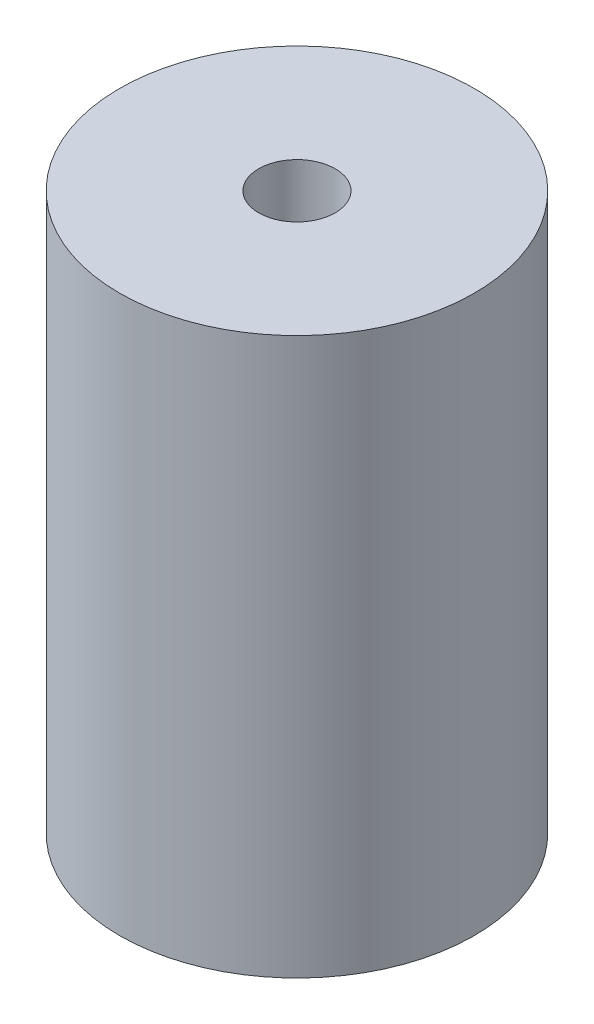
SolidWorks part; units mm, degrees
material "RNX-ELF"
ref_plane "Front Plane" through (0, 0, 0) normal (0, 0, 1) x (1, 0, 0)
ref_plane "Top Plane" through (0, 0, 0) normal (0, 1, 0) x (1, 0, 0)
ref_plane "Right Plane" through (0, 0, 0) normal (1, 0, 0) x (0, 0, -1)
sketch "Sketch1" plane through (0, 0, 0) normal (0, 1, 0) x (1, 0, 0)
  circle A0 centre (0, 0) radius 25.5
  circle A1 centre (0, 0) radius 5.5
  dimension "OD" = 51
  dimension "t" = 20
extrude "Extrude1" add sketch "Sketch1" along normal blind 80
sketch "Sketch2" [suppressed] plane through (0, 38, 0) normal (0, 1, 0) x (-1, 0, 0)
  circle A0 centre (-3.0948, -18.3848) radius 3.8024
sketch "Sketch3" plane through (0, 0, 0) normal (0, 0, 1) x (1, 0, 0)
  line L0 (-25.5, 80) -> (0, 77.769)
  line L1 (25.5, 80) -> (-25.5, 80) construction
  line L2 (0, 77.769) -> (0, 80)
  line L3 (5.5, 80) -> (-5.5, 80) construction
  line L4 (0, 80) -> (-25.5, 80)
  line L5 (-25.5, 40) -> (25.5, 40) construction
  line L6 (-25.5, 80) -> (-25.5, 0) construction
  line L7 (25.5, 0) -> (25.5, 80) construction
  line L8 (0, 2.231) -> (0, 0)
  line L9 (0, 0) -> (-25.5, 0)
  line L10 (-25.5, 0) -> (0, 2.231)
  dimension "D1" = 5
revolve "Cut-Revolve1" [suppressed] cut sketch "Sketch3" angle 360 about L2
